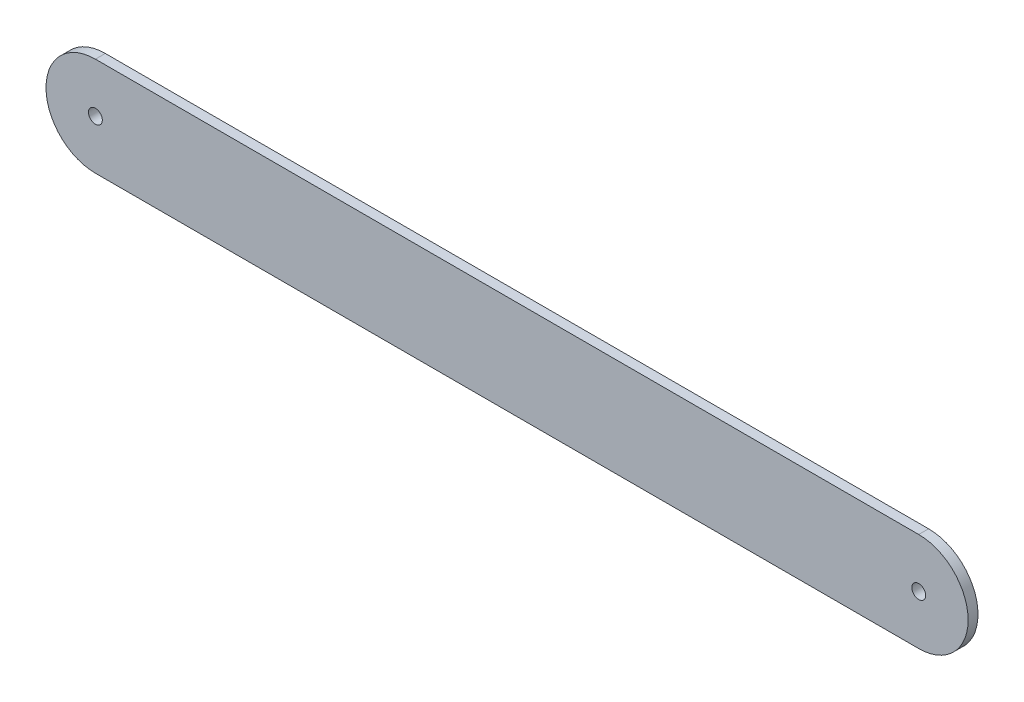
SolidWorks part; units mm, degrees
ref_plane "Plan de face" through (0, 0, 0) normal (0, 0, 1) x (1, 0, 0)
ref_plane "Plan de dessus" through (0, 0, 0) normal (0, 1, 0) x (1, 0, 0)
ref_plane "Plan de droite" through (0, 0, 0) normal (1, 0, 0) x (0, 0, -1)
sketch "Esquisse1" plane through (0, 0, 0) normal (0, 0, 1) x (1, 0, 0)
  line L0 (0, 15) -> (125, 15)
  line L1 (0, -15) -> (125, -15)
  line L2 (0, 42.9033) -> (0, -58.9726) construction
  line L3 (0, 15) -> (0, -15)
  line L4 (125, 15) -> (125, -19.9228) construction
  arc A0 (125, 15) -> (125, -15) centre (125, 0) cw
  circle A1 centre (125, 0) radius 2.1
  dimension "D2" = 4.2
  dimension "D1" = 125
  dimension "D3" = 15
  dimension "D4" = 30
extrude "Boss.-Extru.1" add sketch "Esquisse1" along normal blind 3
mirror "Symétrie1" about plane through (0, 15, 3) normal (1, 0, 0) of bodies 101
